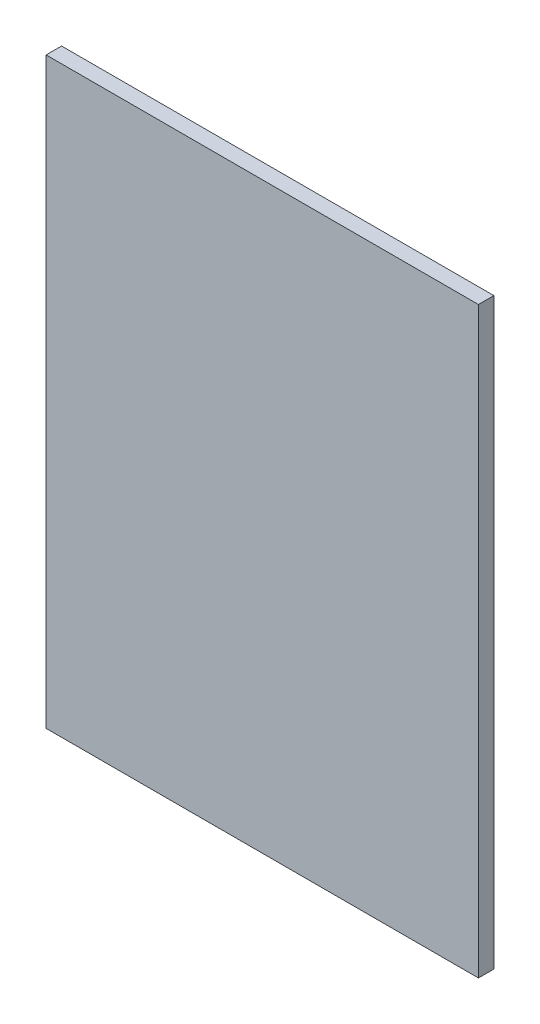
SolidWorks part; units mm, degrees
ref_plane "Front Plane" through (0, 0, 0) normal (0, 0, 1) x (1, 0, 0)
ref_plane "Top Plane" through (0, 0, 0) normal (0, 1, 0) x (1, 0, 0)
ref_plane "Right Plane" through (0, 0, 0) normal (1, 0, 0) x (0, 0, -1)
sketch "Sketch1" plane through (0, 0, 0) normal (0, 0, 1) x (1, 0, 0)
  line L1 (-63, -85) -> (63, -85)
  line L2 (-63, -85) -> (-63, 85)
  line L3 (-63, 85) -> (63, 85)
  line L4 (63, -85) -> (63, 85)
  line L5 (-63, -85) -> (63, 85) construction
  line L6 (-63, 85) -> (63, -85) construction
  point P0 (0, 0)
  dimension "D1" = 170
  dimension "D2" = 126
extrude "Boss-Extrude1" add sketch "Sketch1" along normal blind 4.5 contours L2 L1 L4 L3
